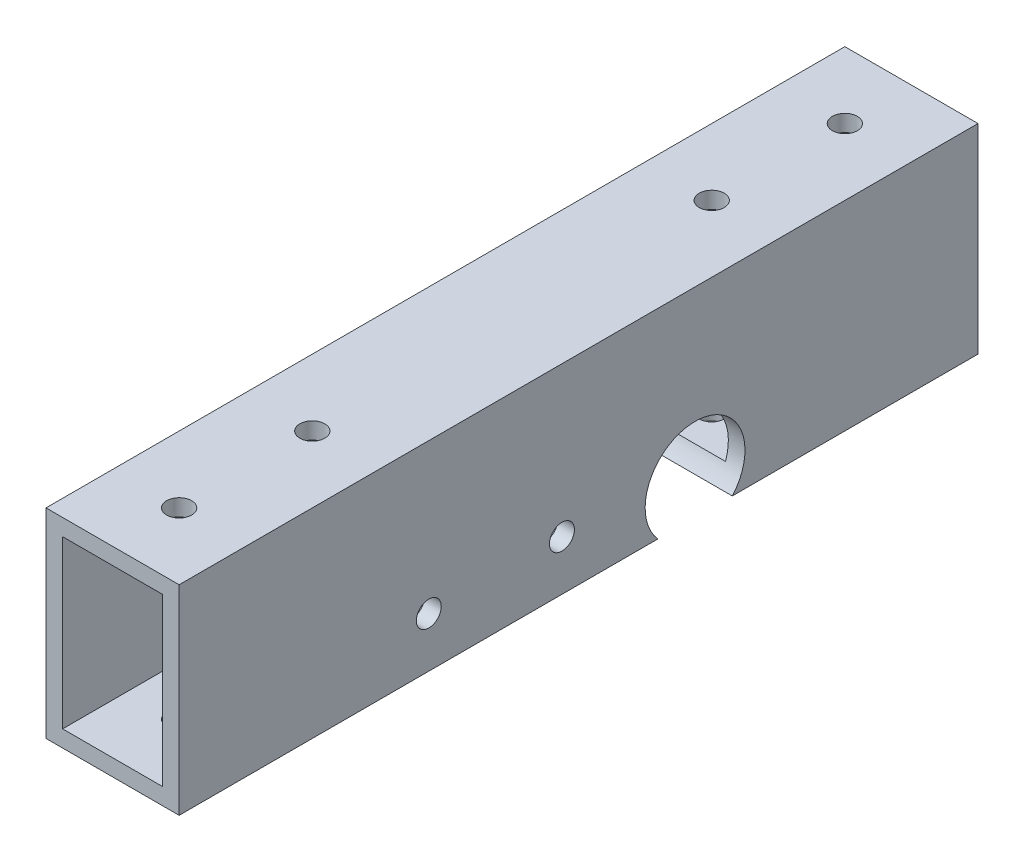
SolidWorks part; units mm, degrees
material "6063-T1"
ref_plane "Front Plane" through (0, 0, 0) normal (0, 0, 1) x (1, 0, 0)
ref_plane "Top Plane" through (0, 0, 0) normal (0, 1, 0) x (1, 0, 0)
ref_plane "Right Plane" through (0, 0, 0) normal (1, 0, 0) x (0, 0, -1)
sketch "Sketch1" plane through (0, 0, 0) normal (0, 0, 1) x (1, 0, 0)
  line L1 (-12.7, 19.05) -> (12.7, 19.05)
  line L2 (-12.7, 19.05) -> (-12.7, -19.05)
  line L3 (-12.7, -19.05) -> (12.7, -19.05)
  line L4 (12.7, 19.05) -> (12.7, -19.05)
  line L5 (-12.7, 19.05) -> (12.7, -19.05) construction
  line L6 (-12.7, -19.05) -> (12.7, 19.05) construction
  point P0 (0, 0)
  dimension "D1" = 25.4
  dimension "D2" = 38.1
extrude "Boss-Extrude1" add sketch "Sketch1" along normal blind 152.4
shell "Shell1" thickness 3.175
sketch "Sketch2" plane through (12.7, 0, 0) normal (1, 0, 0) x (0, 0, -1)
  line L0 (-152.4, -19.05) -> (0, -19.05) construction
  line L1 (0, -19.05) -> (0, 19.05) construction
  circle A0 centre (-53.975, -12.7) radius 9.525
  dimension "D1" = 19.05
  dimension "D2" = 6.35
  dimension "D3" = 53.975
extrude "Cut-Extrude1" cut sketch "Sketch2" against normal through all
sketch "Sketch3" plane through (0, 19.05, 0) normal (0, 1, 0) x (1, 0, 0)
  line L0 (12.7, -152.4) -> (-12.7, -152.4) construction
  circle A0 centre (0, -139.7) radius 2.3812
  circle A1 centre (0, -114.3) radius 2.3812
  dimension "D1" = 4.7625
  dimension "D3" = 4.7625
  dimension "D2" = 12.7
  dimension "D4" = 25.4
extrude "Cut-Extrude2" cut sketch "Sketch3" against normal through all
sketch "Sketch4" plane through (12.7, 0, 0) normal (1, 0, 0) x (0, 0, -1)
  line L0 (-152.4, -19.05) -> (-61.0745, -19.05) construction
  circle A0 centre (-79.375, -9.525) radius 2.3813
  circle A1 centre (-104.775, -9.525) radius 2.3813
  arc A2 (-46.8755, -19.05) -> (-61.0745, -19.05) centre (-53.975, -12.7) ccw construction
  point P9 (0, 0)
  dimension "D1" = 4.7625
  dimension "D2" = 4.7625
  dimension "D3" = 25.4
  dimension "D4" = 25.4
  dimension "D5" = 9.525
extrude "Cut-Extrude3" cut sketch "Sketch4" against normal through all
sketch "Sketch5" plane through (0, 19.05, 0) normal (0, 1, 0) x (1, 0, 0)
  line L0 (12.7, 0) -> (-12.7, 0) construction
  circle A0 centre (0, -12.7) radius 2.3813
  circle A1 centre (0, -38.1) radius 2.3812
  point P6 (0, 0)
  point P7 (0, 0)
  dimension "D1" = 4.7625
  dimension "D4" = 4.7625
  dimension "D2" = 12.7
  dimension "D3" = 25.4
extrude "Cut-Extrude4" cut sketch "Sketch5" against normal through all
